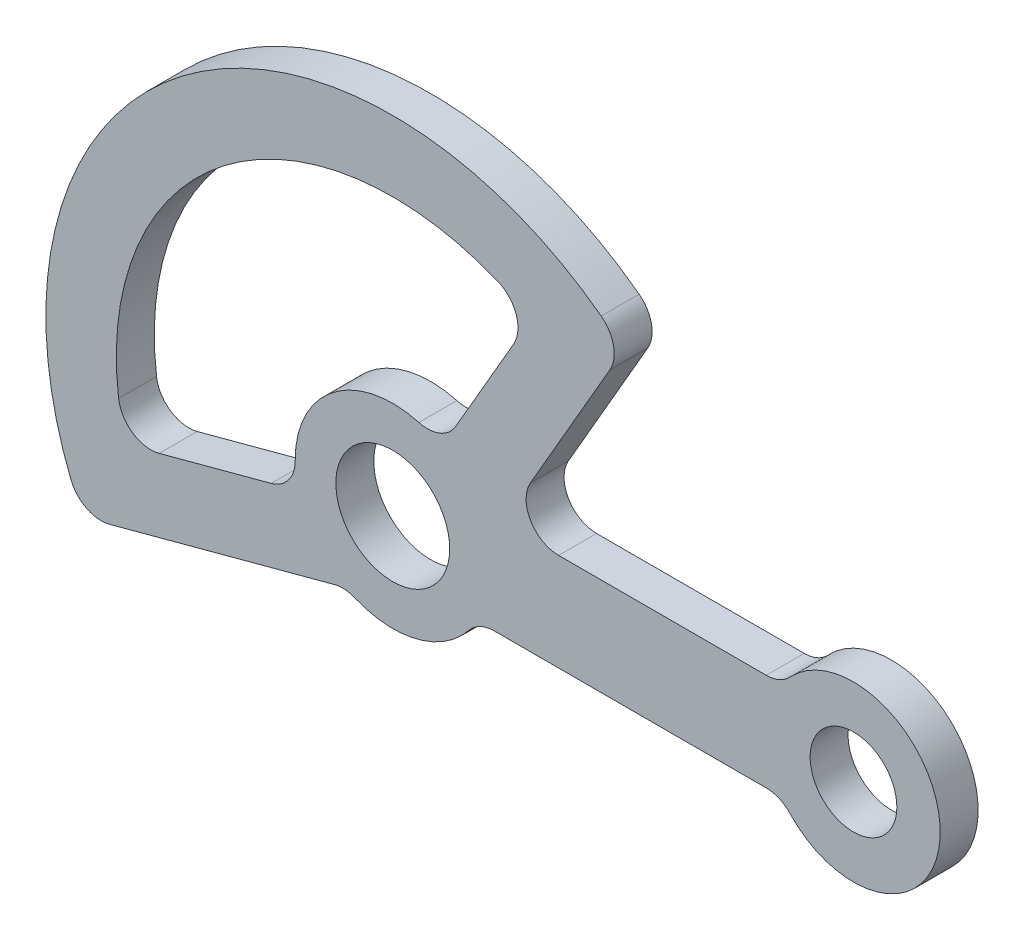
SolidWorks part; units mm, degrees
ref_plane "Front Plane" through (0, 0, 0) normal (0, 0, 1) x (1, 0, 0)
ref_plane "Top Plane" through (0, 0, 0) normal (0, 1, 0) x (1, 0, 0)
ref_plane "Right Plane" through (0, 0, 0) normal (1, 0, 0) x (0, 0, -1)
sketch "Sketch1" plane through (0, 0, 0) normal (0, 0, 1) x (1, 0, 0)
  line L0 (11.619, 20.1246) -> (22.2991, 38.6232)
  line L1 (-22.4461, -6.0144) -> (-43.0786, -11.5429)
  line L2 (-10.7986, -16.3521) -> (-52.2495, -27.4588)
  line L3 (0, -55) -> (0, 55) construction
  line L4 (55, 0) -> (-55, 0) construction
  line L5 (25.4034, 18) -> (40.0463, 43.3623)
  line L6 (68.9065, 9) -> (30.5996, 9)
  line L7 (68.9065, -9) -> (18.735, -9)
  line L9 (0, 0) -> (25.5, 44.1673) construction
  line L10 (0, 0) -> (-49.2622, -13.1998) construction
  line L11 (8.5659, -11.1634) -> (-57.1658, -28.7761) construction
  line L12 (8.5659, -11.1634) -> (42.5912, 47.7702) construction
  arc A0 (4.8171, 17.3435) -> (-17.9993, -0.1641) centre (0, 0) ccw
  circle A1 centre (0, 0) radius 10.5
  arc A2 (19.3833, 47.1729) -> (-50.5823, -6.5136) centre (0, 0) ccw
  arc A3 (38.4554, 51.1584) -> (-59.3682, -23.9043) centre (0, 0) ccw
  arc A4 (73.2957, -10.9091) -> (73.2957, 10.9091) centre (85, 0) ccw
  circle A5 centre (85, 0) radius 8
  arc A6 (-6.9343, -16.6107) -> (14.0512, -11.25) centre (0, 0) ccw
  arc A7 (68.9065, 9) -> (73.2957, 10.9091) centre (68.9065, 15) ccw
  arc A8 (68.9065, -9) -> (73.2957, -10.9091) centre (68.9065, -15) cw
  arc A9 (4.8171, 17.3435) -> (11.619, 20.1246) centre (6.4228, 23.1246) ccw
  arc A10 (-22.4461, -6.0144) -> (-17.9993, -0.1641) centre (-23.999, -0.2189) ccw
  arc A11 (-10.7986, -16.3521) -> (-6.9343, -16.6107) centre (-9.2457, -22.1476) cw
  arc A12 (14.0512, -11.25) -> (18.735, -9) centre (18.735, -15) cw
  arc A13 (25.4034, 18) -> (30.5996, 9) centre (30.5996, 15) ccw
  arc A14 (42.5912, 47.7702) -> (-57.1658, -28.7761) centre (0, 0) ccw construction
  arc A15 (40.0463, 43.3623) -> (38.4554, 51.1584) centre (34.8502, 46.3623) ccw
  arc A16 (-59.3682, -23.9043) -> (-52.2495, -27.4588) centre (-53.8024, -21.6633) ccw
  arc A17 (25.5, 44.1673) -> (-49.2622, -13.1998) centre (0, 0) ccw construction
  arc A18 (-43.0786, -11.5429) -> (-50.5823, -6.5136) centre (-44.6315, -5.7473) cw
  arc A19 (22.2991, 38.6232) -> (19.3833, 47.1729) centre (17.103, 41.6232) ccw
  point P32 (-8.661, -15.7793)
  dimension "D1" = 36
  dimension "D2" = 21
  dimension "D3" = 51
  dimension "D7" = 32
  dimension "D8" = 16
  dimension "D12" = 12
  dimension "D13" = 6
  dimension "D4" = 30
  dimension "D5" = 15
  dimension "D9" = 9
  dimension "D10" = 18
  dimension "D11" = 85
  dimension "D6" = 13
extrude "Boss-Extrude1" add sketch "Sketch1" along normal blind 7
